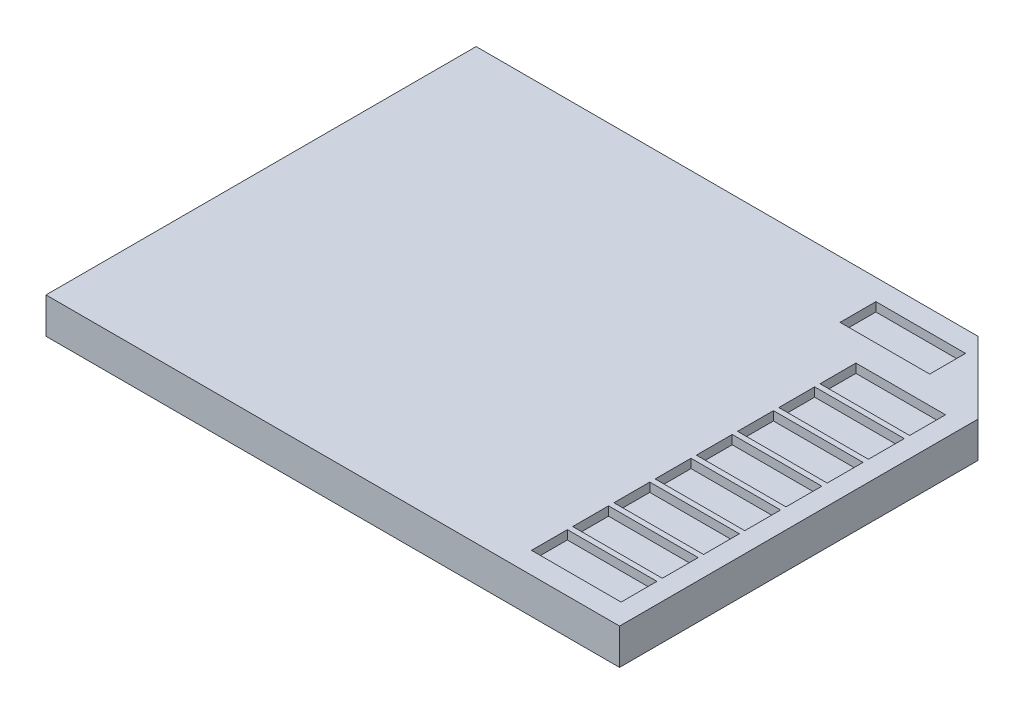
SolidWorks part; units mm, degrees
ref_plane "前视基准面" through (0, 0, 0) normal (0, 0, 1) x (1, 0, 0)
ref_plane "上视基准面" through (0, 0, 0) normal (0, 1, 0) x (1, 0, 0)
ref_plane "右视基准面" through (0, 0, 0) normal (1, 0, 0) x (0, 0, -1)
sketch "草图1" plane through (0, 0, 0) normal (0, 1, 0) x (1, 0, 0)
  line L0 (-46.6975, 0) -> (49.1233, 0) construction
  line L1 (0, 29.4291) -> (0, -22.7948) construction
  line L3 (-16, 12) -> (16, 12)
  line L4 (-16, 12) -> (-16, -12)
  line L5 (-16, -12) -> (16, -12)
  line L6 (16, 12) -> (16, -12)
  dimension "D1" = 32
  dimension "D2" = 24
extrude "拉伸1" add sketch "草图1" along normal blind 2
sketch "草图2" plane through (0, 2, 0) normal (0, 1, 0) x (-1, 0, 0)
  line L0 (-16, -12) -> (-12, -12)
  line L1 (-16, -12) -> (16, -12) construction
  line L2 (-12, -12) -> (-16, -8)
  line L3 (-16, 12) -> (-16, -12) construction
  line L4 (-16, -8) -> (-16, -12)
  dimension "D1" = 20
  dimension "D2" = 28
extrude "切除-拉伸1" cut sketch "草图2" against normal blind 2
sketch "草图3" plane through (0, 2, 0) normal (0, 1, 0) x (-1, 0, 0)
  line L0 (-14.8854, 6.4983) -> (-9.8854, 6.4983)
  line L1 (-14.8854, 8.7983) -> (-9.8854, 8.7983)
  line L2 (-14.8854, 8.7983) -> (-14.8854, 10.7983)
  line L3 (-14.8854, 10.7983) -> (-9.8854, 10.7983)
  line L4 (-9.8854, 8.7983) -> (-9.8854, 10.7983)
  line L5 (-14.8854, 6.4983) -> (-14.8854, 8.4983)
  line L6 (-14.8854, 8.4983) -> (-9.8854, 8.4983)
  line L7 (-9.8854, 6.4983) -> (-9.8854, 8.4983)
  line L8 (-14.8854, 4.1983) -> (-9.8854, 4.1983)
  line L9 (-14.8854, 4.1983) -> (-14.8854, 6.1983)
  line L10 (-14.8854, 6.1983) -> (-9.8854, 6.1983)
  line L11 (-9.8854, 4.1983) -> (-9.8854, 6.1983)
  line L12 (-14.8854, 1.8983) -> (-9.8854, 1.8983)
  line L13 (-14.8854, 1.8983) -> (-14.8854, 3.8983)
  line L14 (-14.8854, 3.8983) -> (-9.8854, 3.8983)
  line L15 (-9.8854, 1.8983) -> (-9.8854, 3.8983)
  line L16 (-14.8854, -0.4017) -> (-9.8854, -0.4017)
  line L17 (-14.8854, -0.4017) -> (-14.8854, 1.5983)
  line L18 (-14.8854, 1.5983) -> (-9.8854, 1.5983)
  line L19 (-9.8854, -0.4017) -> (-9.8854, 1.5983)
  line L20 (-14.8854, -2.7017) -> (-9.8854, -2.7017)
  line L21 (-14.8854, -2.7017) -> (-14.8854, -0.7017)
  line L22 (-14.8854, -0.7017) -> (-9.8854, -0.7017)
  line L23 (-9.8854, -2.7017) -> (-9.8854, -0.7017)
  line L24 (-14.8854, -5.0017) -> (-9.8854, -5.0017)
  line L25 (-14.8854, -5.0017) -> (-14.8854, -3.0017)
  line L26 (-14.8854, -3.0017) -> (-9.8854, -3.0017)
  line L27 (-9.8854, -5.0017) -> (-9.8854, -3.0017)
  line L28 (-14.8854, -7.3017) -> (-9.8854, -7.3017)
  line L29 (-14.8854, -7.3017) -> (-14.8854, -5.3017)
  line L30 (-14.8854, -5.3017) -> (-9.8854, -5.3017)
  line L31 (-9.8854, -7.3017) -> (-9.8854, -5.3017)
  line L32 (-12.4774, -10.827) -> (-7.4774, -10.827)
  line L33 (-12.4774, -10.827) -> (-12.4774, -8.827)
  line L34 (-12.4774, -8.827) -> (-7.4774, -8.827)
  line L35 (-7.4774, -10.827) -> (-7.4774, -8.827)
  dimension "D1" = 2
  dimension "D2" = 5
extrude "切除-拉伸2" cut sketch "草图3" against normal blind 0.5
